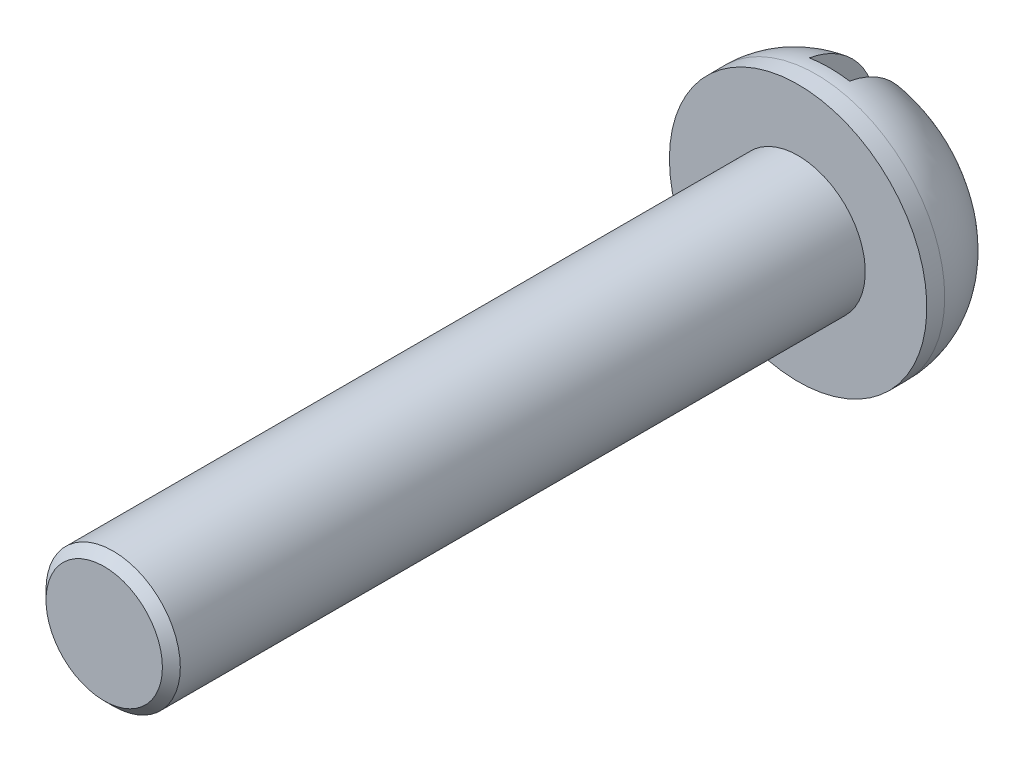
SolidWorks part; units mm, degrees
ref_plane "Plano frontal" through (0, 0, 0) normal (0, 0, 1) x (1, 0, 0)
ref_plane "Plano superior" through (0, 0, 0) normal (0, 1, 0) x (1, 0, 0)
ref_plane "Plano direito" through (0, 0, 0) normal (1, 0, 0) x (0, 0, -1)
sketch "Esboço1" plane through (0, 0, 0) normal (0, 0, 1) x (1, 0, 0)
  circle A0 centre (0, 0) radius 1.5
  dimension "D1" = 3
extrude "Ressalto-extrusão1" add sketch "Esboço1" along normal blind 17.7
sketch "Esboço2" plane through (0, 0, 0) normal (0, 0, -1) x (-1, 0, 0)
  circle A0 centre (0, 0) radius 2.875
  dimension "D1" = 5.75
extrude "Ressalto-extrusão2" add sketch "Esboço2" against normal blind 2.2
fillet "Filete1" radius 1.8 1 edges at (-2.875, 0, 0)
sketch "Esboço3" plane through (0, 0, 0) normal (0, 0, -1) x (-1, 0, 0)
  line L1 (0.45, 3.0608) -> (-0.45, 3.0608)
  line L2 (0.45, 3.0608) -> (0.45, -3.0608)
  line L3 (0.45, -3.0608) -> (-0.45, -3.0608)
  line L4 (-0.45, 3.0608) -> (-0.45, -3.0608)
  line L5 (0.45, 3.0608) -> (-0.45, -3.0608) construction
  line L6 (0.45, -3.0608) -> (-0.45, 3.0608) construction
  point P0 (0, 0)
  dimension "D1" = 0.9
extrude "Corte-extrusão1" cut sketch "Esboço3" against normal blind 1.5
chamfer "Chanfro1" distance 0.2 angle 45 1 edges at (1.5, 0, 17.7)
